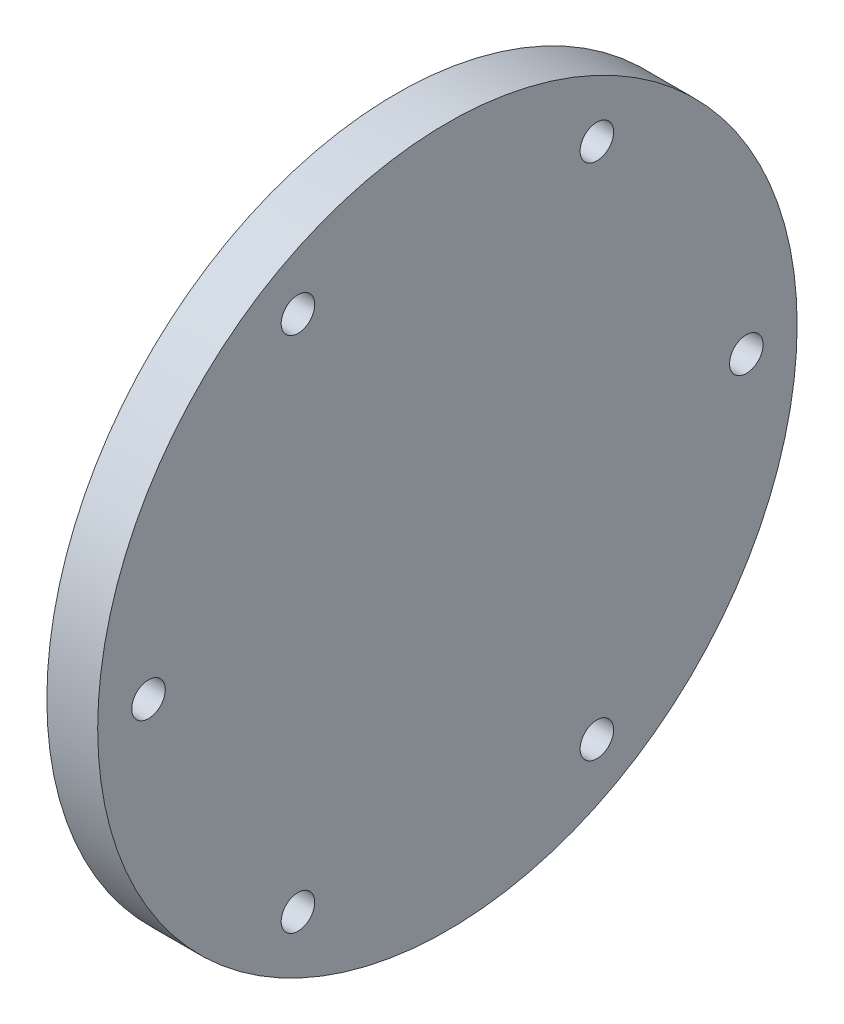
SolidWorks part; units mm, degrees
material "Copper"
ref_plane "Front Plane" through (0, 0, 0) normal (0, 0, 1) x (1, 0, 0)
ref_plane "Top Plane" through (0, 0, 0) normal (0, 1, 0) x (1, 0, 0)
ref_plane "Right Plane" through (0, 0, 0) normal (1, 0, 0) x (0, 0, -1)
sketch "Axial profile (mm)" plane through (0, 0, 0) normal (0, 0, 1) x (1, 0, 0)
  line L0 (-110, 0) -> (75, 0) construction
  line L1 (163.7, 0) -> (168.7, 0)
  line L2 (168.7, 0) -> (168.7, 34.4)
  line L3 (168.7, 34.4) -> (163.7, 34.4)
  line L4 (163.7, 34.4) -> (163.7, 0)
revolve "Full revolution" add sketch "Axial profile (mm)" angle 360 about L0
sketch "Sketch2" plane through (0, 0, 0) normal (1, 0, 0) x (0, 0, -1)
  circle A0 centre (-29.4, 0) radius 1.65
  circle A1 centre (14.7, -25.4611) radius 1.65
  circle A2 centre (14.7, 25.4611) radius 1.65
extrude "Axial holes" cut sketch "Sketch2" along normal through all and the other way through all
sketch "Sketch3" plane through (0, 0, 0) normal (1, 0, 0) x (0, 0, -1)
  circle A0 centre (29.4, 0) radius 1.65
  circle A1 centre (-14.7, 25.4611) radius 1.65
  circle A2 centre (-14.7, -25.4611) radius 1.65
extrude "Cut-Extrude2" cut sketch "Sketch3" along normal blind 3.5 from offset 165.2
